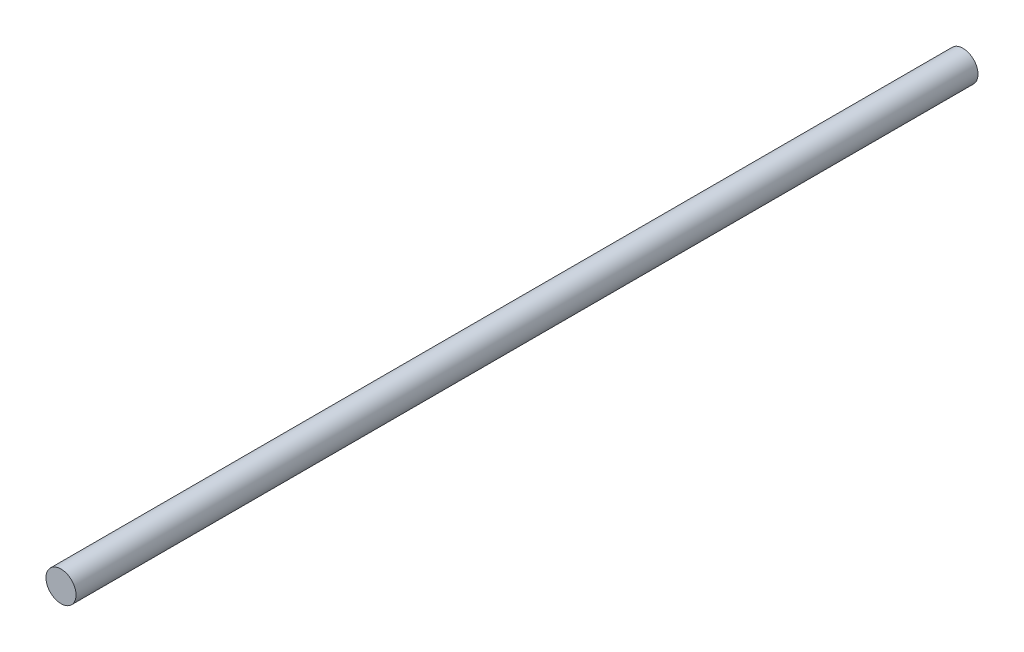
SolidWorks part; units mm, degrees
material "Cast Carbon Steel"
ref_plane "Front Plane" through (0, 0, 0) normal (0, 0, 1) x (1, 0, 0)
ref_plane "Top Plane" through (0, 0, 0) normal (0, 1, 0) x (1, 0, 0)
ref_plane "Right Plane" through (0, 0, 0) normal (1, 0, 0) x (0, 0, -1)
sketch "Sketch1" plane through (0, 0, 0) normal (0, 0, 1) x (1, 0, 0)
  circle A0 centre (0, 0) radius 12.065
  dimension "D1" = 24.13
extrude "Boss-Extrude1" add sketch "Sketch1" along normal blind 723.9
